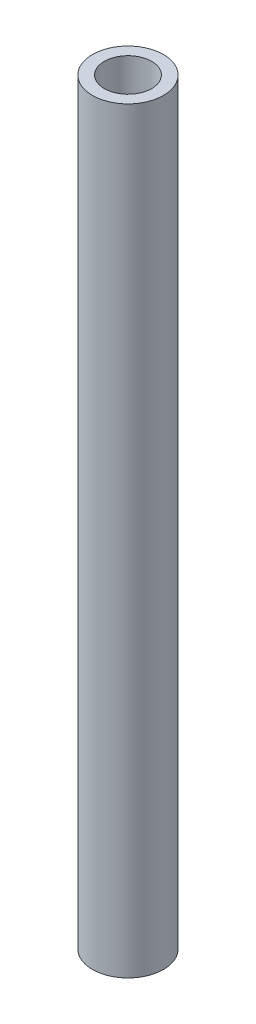
SolidWorks part; units mm, degrees
ref_plane "Front Plane" through (0, 0, 0) normal (0, 0, 1) x (1, 0, 0)
ref_plane "Top Plane" through (0, 0, 0) normal (0, 1, 0) x (1, 0, 0)
ref_plane "Right Plane" through (0, 0, 0) normal (1, 0, 0) x (0, 0, -1)
sketch "Sketch1" plane through (0, 0, 0) normal (0, 1, 0) x (1, 0, 0)
  circle A0 centre (0, 0) radius 4.7625
  circle A1 centre (0, 0) radius 3.175
  dimension "D1" = 9.525
  dimension "D2" = 6.35
extrude "Boss-Extrude1" add sketch "Sketch1" along normal blind 101.6
